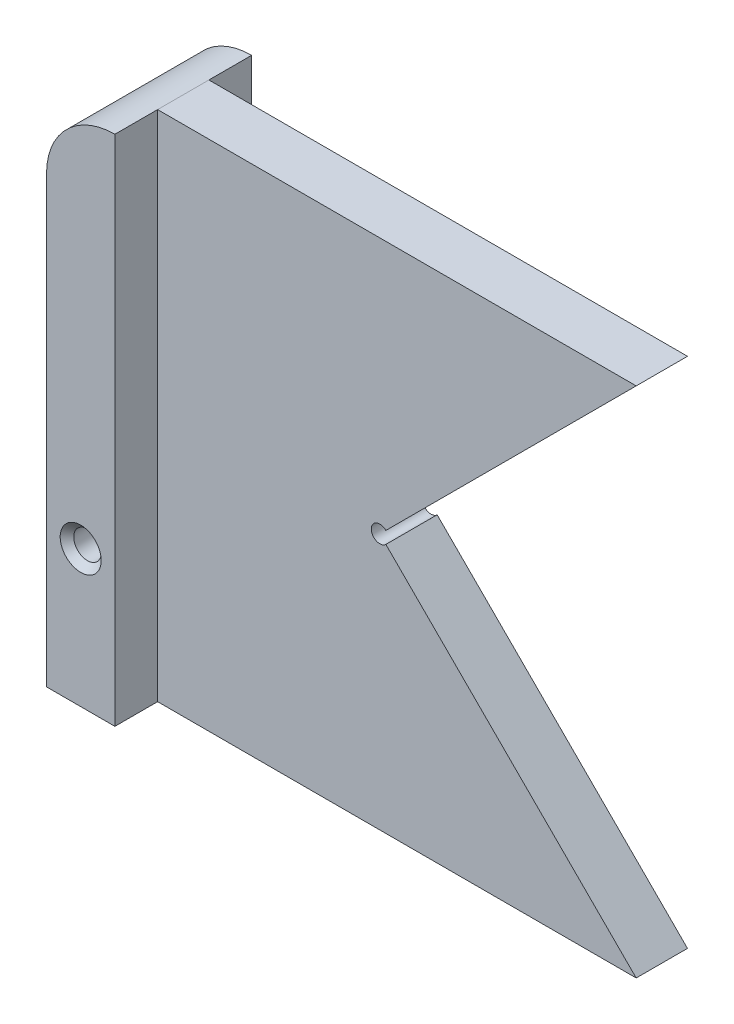
SolidWorks part; units mm, degrees
material "Plain Carbon Steel"
ref_plane "Front" through (0, 0, 0) normal (0, 0, 1) x (1, 0, 0)
ref_plane "Top" through (0, 0, 0) normal (0, 1, 0) x (1, 0, 0)
ref_plane "Right" through (0, 0, 0) normal (1, 0, 0) x (0, 0, -1)
sketch "Sketch2" plane through (0, 0, 0) normal (0, 0, 1) x (1, 0, 0)
  line L0 (0, 0) -> (0, 95.25)
  line L1 (0, 95.25) -> (101.6, 95.25)
  line L2 (101.6, 95.25) -> (53.975, 47.625)
  line L3 (53.975, 47.625) -> (101.6, 0)
  line L4 (101.6, 0) -> (0, 0)
  dimension "D1" = 95.25
  dimension "D2" = 101.6
  dimension "D3" = 45
  dimension "D4" = 47.625
extrude "Boss-Extrude1" add sketch "Sketch2" along normal mid plane 25.4
hole_wizard "1/8 (0.125) Diameter Hole1" positions "Sketch4" profile "Sketch3" hole size "1/8" standard "ANSI Inch" end condition through all
sketch "Sketch4" plane through (0, 0, 12.7) normal (0, 0, 1) x (1, 0, 0)
  point P0 (53.975, 47.625)
sketch "Sketch3" plane through (53.975, 47.625, 12.7) normal (1, 0, 0) x (0, -1, 0)
  line L0 (0, 0) -> (0, 25.4)
  line L1 (0, 25.4) -> (1.5875, 25.4)
  line L2 (1.5875, 25.4) -> (1.5875, 0)
  line L5 (1.5875, 0) -> (0, 0)
  line L11 (0, -6.35) -> (0, 107.95) construction
  dimension "Thru Hole Dia." = 3.175
  dimension "Thru Hole Depth" = 25.4
fillet "Fillet1" radius 12.7 1 edges at (0, 95.25, 0)
hole_wizard "1/4-20 Tapped Hole1" positions "Sketch6" profile "Sketch5" tap size "1/4-20" standard "ANSI Inch" end condition through all
sketch "Sketch6" plane through (0, 0, 12.7) normal (0, 0, 1) x (1, 0, 0)
  line L0 (0, 0) -> (101.6, 0) construction
  line L1 (0, 82.55) -> (0, 0) construction
  point P0 (6.35, 25.4)
  dimension "D1" = 25.4
  dimension "D2" = 6.35
cosmetic thread "Hole Thread1" parameters "D2"=6.35
sketch "Sketch5" plane through (6.35, 25.4, 12.7) normal (1, 0, 0) x (0, -1, 0)
  line L0 (0, 0) -> (0, 25.4)
  line L1 (0, 25.4) -> (3.81, 25.4)
  line L2 (2.5527, 24.1427) -> (2.5527, 1.2573)
  line L3 (2.5527, 1.2573) -> (3.81, 0)
  line L5 (3.81, 0) -> (0, 0)
  line L6 (-2.5527, 1.2573) -> (-3.81, 0) construction
  line L7 (3.81, 25.4) -> (2.5527, 24.1427)
  line L8 (-3.81, 25.4) -> (-2.5527, 24.1427) construction
  line L11 (0, -6.35) -> (0, 107.95) construction
  dimension "Thru Tap Drill Dia." = 5.1054
  dimension "Thru Tap Drill Depth" = 25.4
  dimension "Near C'Sink Dia." = 7.62
  dimension "Near C'Sink Angle" = 90
  dimension "Far C'Sink Dia." = 7.62
  dimension "Far C'Sink Angle" = 90
hole_wizard "1/4-20 Tapped Hole2" positions "Sketch8" profile "Sketch7" tap size "1/4-20" standard "ANSI Inch"
sketch "Sketch8" plane through (0, 0, 0) normal (-1, 0, 0) x (0, 0, 1)
  point P0 (0, 41.275)
  point P2 (0, 9.525)
  dimension "D1" = 9.525
  dimension "D2" = 31.75
sketch "Sketch7" plane through (0, 41.275, 0) normal (0, 1, 0) x (0, 0, 1)
  line L0 (0, 0) -> (0, 17.4088)
  line L1 (0, 17.4088) -> (2.5527, 15.875)
  line L2 (2.5527, 15.875) -> (2.5527, 1.2573)
  line L3 (2.5527, 1.2573) -> (3.81, 0)
  line L5 (3.81, 0) -> (0, 0)
  line L6 (-2.5527, 1.2573) -> (-3.81, 0) construction
  line L10 (0, 17.4088) -> (-2.5527, 15.875) construction
  line L11 (0, -6.35) -> (0, 107.95) construction
  dimension "Tap Drill Dia." = 5.1054
  dimension "Tap Drill Depth" = 15.875
  dimension "Near C'Sink Dia." = 7.62
  dimension "Near C'Sink Angle" = 90
  dimension "Drill Angle" = 118
cosmetic thread "Hole Thread2" parameters "D1"=12.7, "D2"=6.35
cosmetic thread "Hole Thread3" parameters "D1"=12.7, "D2"=6.35
sketch "Sketch10" plane through (0, 95.25, 0) normal (0, 1, 0) x (1, 0, 0)
  line L0 (0, 0) -> (101.6, 0) construction
  line L1 (101.6, -12.7) -> (101.6, 12.7) construction
  line L2 (12.7, 12.7) -> (12.7, -12.7) construction
  line L3 (101.6, 12.7) -> (12.7, 12.7)
  line L4 (101.6, 12.7) -> (101.6, 4.7625)
  line L5 (101.6, 4.7625) -> (12.7, 4.7625)
  line L6 (12.7, 12.7) -> (12.7, 4.7625)
  line L8 (101.6, -12.7) -> (12.7, -12.7)
  line L9 (101.6, -12.7) -> (101.6, -4.7625)
  line L10 (101.6, -4.7625) -> (12.7, -4.7625)
  line L11 (12.7, -12.7) -> (12.7, -4.7625)
  dimension "D1" = 7.9375
extrude "Cut-Extrude1" cut sketch "Sketch10" against normal through all
